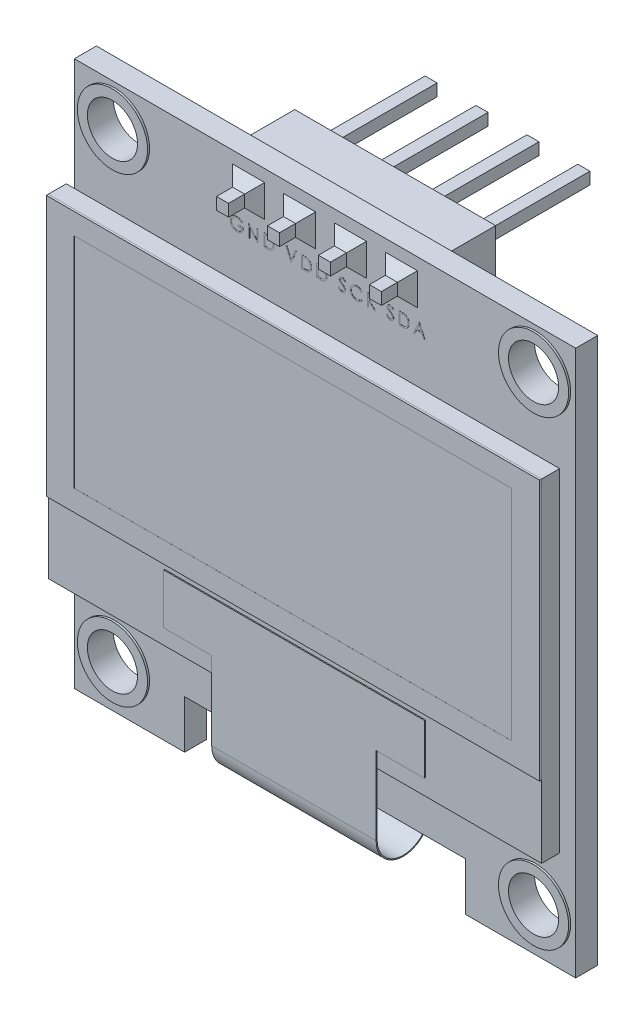
SolidWorks part; units mm, degrees
ref_plane "Front" through (0, 0, 0) normal (0, 0, 1) x (1, 0, 0)
ref_plane "Top" through (0, 0, 0) normal (0, 1, 0) x (1, 0, 0)
ref_plane "Right" through (0, 0, 0) normal (1, 0, 0) x (0, 0, -1)
sketch "Sketch1" plane through (0, 0, 0) normal (0, 0, 1) x (1, 0, 0)
  line L0 (7, -27.2) -> (12.5, -27.2)
  line L1 (-12.5, 0) -> (12.5, 0)
  line L2 (-12.5, 0) -> (-12.5, -27.2)
  line L3 (-12.5, -27.2) -> (-7, -27.2)
  line L4 (12.5, 0) -> (12.5, -27.2)
  line L5 (0, 0) -> (0, -2) construction
  line L6 (-7, -27.2) -> (-7, -24.8)
  line L7 (-7, -24.8) -> (7, -24.8)
  line L8 (7, -27.2) -> (7, -24.8)
  line L9 (-10.5, -2) -> (10.5, -2) construction
  line L10 (-10.5, -2) -> (-10.5, -25) construction
  line L11 (-10.5, -25) -> (10.5, -25) construction
  line L12 (10.5, -2) -> (10.5, -25) construction
  circle A0 centre (-10.5, -2) radius 1.25
  circle A1 centre (10.5, -2) radius 1.25
  circle A2 centre (10.5, -25) radius 1.25
  circle A3 centre (-10.5, -25) radius 1.25
  dimension "D5" = 2.5
  dimension "D1" = 25
  dimension "D2" = 27.2
  dimension "D3" = 5.5
  dimension "D4" = 2.4
  dimension "D6" = 2
  dimension "D7" = 21
  dimension "D8" = 23
extrude "Boss-Extrude1" add sketch "Sketch1" along normal blind 1.1
sketch "Sketch2" plane through (0, 0, 1.1) normal (0, 0, 1) x (1, 0, 0)
  line L0 (-1.57, -1.1) -> (-0.97, -1.1)
  line L1 (-4.11, -1.1) -> (-3.51, -1.1)
  line L2 (-4.11, -1.1) -> (-4.11, -1.7)
  line L3 (-4.11, -1.7) -> (-3.51, -1.7)
  line L4 (-3.51, -1.1) -> (-3.51, -1.7)
  line L5 (-1.57, -1.1) -> (-1.57, -1.7)
  line L6 (-1.57, -1.7) -> (-0.97, -1.7)
  line L7 (-0.97, -1.1) -> (-0.97, -1.7)
  line L8 (0.97, -1.1) -> (1.57, -1.1)
  line L9 (0.97, -1.1) -> (0.97, -1.7)
  line L10 (0.97, -1.7) -> (1.57, -1.7)
  line L11 (1.57, -1.1) -> (1.57, -1.7)
  line L12 (3.51, -1.1) -> (4.11, -1.1)
  line L13 (3.51, -1.1) -> (3.51, -1.7)
  line L14 (3.51, -1.7) -> (4.11, -1.7)
  line L15 (4.11, -1.1) -> (4.11, -1.7)
  line L16 (-0.97, -1.4) -> (0.97, -1.4) construction
  line L17 (0, 0) -> (0, -1.4) construction
  dimension "D2" = 0.6
  dimension "D3" = 2.54
  dimension "D4" = 1.4
  dimension "D1" = 4
extrude "Boss-Extrude2" add sketch "Sketch2" against normal offset from surface 8 and the other way blind 1.3 up to face at (11.75, -25, 0) offset beyond the face yes
chamfer "Chamfer1" distance 0.5 angle 45 16 edges at (-3.81, -1.7, 1.1) (-4.11, -1.4, 1.1) (-3.51, -1.4, 1.1) (-3.81, -1.1, 1.1) (-1.27, -1.7, 1.1) (-1.57, -1.4, 1.1) (-0.97, -1.4, 1.1) (-1.27, -1.1, 1.1) (3.81, -1.7, 1.1) (3.51, -1.4, 1.1) (4.11, -1.4, 1.1) (3.81, -1.1, 1.1) (1.57, -1.4, 1.1) (1.27, -1.7, 1.1) (0.97, -1.4, 1.1) (1.27, -1.1, 1.1)
sketch "Sketch3" plane through (0, 0, 0) normal (0, 0, -1) x (-1, 0, 0)
  line L0 (-5.01, -1.4) -> (-4.11, -1.4) construction
  line L1 (-5.01, -0.2) -> (5.01, -0.2)
  line L2 (-5.01, -0.2) -> (-5.01, -2.6)
  line L3 (-5.01, -2.6) -> (5.01, -2.6)
  line L4 (5.01, -0.2) -> (5.01, -2.6)
  line L5 (-4.11, -1.1) -> (-4.11, -1.7) construction
  line L6 (4.11, -1.4) -> (5.01, -1.4) construction
  line L7 (4.11, -1.7) -> (4.11, -1.1) construction
  line L8 (-3.51, -1.1) -> (-4.11, -1.1) construction
  point P12 (-3.81, -1.1)
  dimension "D1" = 2.4
  dimension "D2" = 1.2
extrude "Boss-Extrude3" add sketch "Sketch3" along normal blind 2.4 separate body
sketch "Sketch4" plane through (0, 0, 1.1) normal (0, 0, 1) x (1, 0, 0)
  line L0 (12.5, 0) -> (-12.5, 0) construction
  line L1 (-12.3, -5) -> (12.3, -5)
  line L2 (-12.3, -5) -> (-12.3, -21.6)
  line L3 (-12.3, -21.6) -> (12.3, -21.6)
  line L4 (12.3, -5) -> (12.3, -21.6)
  point P4 (0, -5)
  dimension "D1" = 24.6
  dimension "D2" = 16.6
  dimension "D3" = 5
extrude "Boss-Extrude4" add sketch "Sketch4" along normal blind 0.9 from offset 0.6
sketch "Sketch5" plane through (0, 0, 2.6) normal (0, 0, 1) x (1, 0, 0)
  line L0 (12.3, -21.6) -> (12.3, -5) construction
  line L1 (-12.3, -5) -> (12.3, -5)
  line L2 (-12.3, -5) -> (-12.3, -18)
  line L3 (-12.3, -18) -> (12.3, -18)
  line L4 (12.3, -5) -> (12.3, -18)
  dimension "D1" = 13
extrude "Boss-Extrude5" add sketch "Sketch5" along normal blind 0.1
sketch "Sketch6" plane through (0, 0, 1.7) normal (0, 0, -1) x (-1, 0, 0)
  line L8 (11.3, -20.6) -> (11.3, -6)
  line L9 (11.3, -6) -> (-11.3, -6)
  line L10 (-11.3, -6) -> (-11.3, -20.6)
  line L11 (-11.3, -20.6) -> (11.3, -20.6)
  line L12 (11.3, -20.6) -> (11.3, -6)
  line L13 (11.3, -6) -> (-11.3, -6)
  line L14 (-11.3, -6) -> (-11.3, -20.6)
  line L15 (-11.3, -20.6) -> (11.3, -20.6)
  dimension "D1" = 1
extrude "Boss-Extrude6" add sketch "Sketch6" along normal up to surface (0.6 mm away) separate body up to face at (-3.81, -1.4, 1.1)
sketch "Sketch7" plane through (0, 0, 0) normal (1, 0, 0) x (0, 0, -1)
  line L0 (-2.6, -18.3) -> (-2.6, -21.6)
  line L1 (-2.6, -21.6) -> (-2.6, -5) construction
  line L3 (-2.6, -21.6) -> (-2.6, -24.7)
  line L4 (0, -19.2) -> (0, -24.7)
  line L5 (0, -27.2) -> (0, 0) construction
  line L6 (-1.3, -26) -> (-1.3, -27.2) construction
  line L7 (-1.3, -27.2) -> (-1.1, -27.2) construction
  line L8 (-1.1, -27.2) -> (0, -27.2) construction
  arc A0 (-2.6, -24.7) -> (0, -24.7) centre (-1.3, -24.7) ccw
  dimension "D1" = 1.2
  dimension "D2" = 0.3
  dimension "D3" = 8
extrude "Extrude-Thin1" add sketch "Sketch7" along normal mid plane 21 separate body thin
ref_plane "Plane1" through (0, 0, 1.3) normal (0, 0, 1) x (1, 0, 0)
sketch "Sketch9" plane through (0, 0, 1.3) normal (0, 0, 1) x (1, 0, 0)
  line L0 (-6.5, -18.3) -> (-6.5, -20.8)
  line L1 (10.5, -18.3) -> (-10.5, -18.3) construction
  line L2 (-6.5, -20.8) -> (-4.1, -20.8)
  line L3 (-4.1, -20.8) -> (-4.1, -26.05)
  line L4 (-10.5, -26.05) -> (10.5, -26.05) construction
  line L5 (-4.1, -26.05) -> (4.1, -26.05)
  line L6 (4.1, -26.05) -> (4.1, -20.8)
  line L7 (4.1, -20.8) -> (6.5, -20.8)
  line L8 (6.5, -20.8) -> (6.5, -18.3)
  line L9 (6.5, -18.3) -> (-6.5, -18.3)
  point P4 (0, -18.3)
  dimension "D1" = 13
  dimension "D2" = 2.5
  dimension "D3" = 8.2
extrude "Cut-Extrude1" cut sketch "Sketch9" along normal blind 21 flip side to cut
sketch "Sketch10" plane through (0, 0, 1.3) normal (0, 0, 1) x (1, 0, 0)
  line L1 (4.1, -26.05) -> (4.1, -25.55)
  line L2 (4.1, -25.55) -> (10.5, -22.2)
  line L3 (10.5, -19.2) -> (10.5, -24.7) construction
  line L4 (10.5, -22.2) -> (10.5, -19.2)
  line L5 (10.5, -19.2) -> (-10.5, -19.2)
  line L6 (-10.5, -19.2) -> (-10.5, -24.7) construction
  line L7 (-10.5, -19.2) -> (-10.5, -22.2)
  line L8 (-10.5, -22.2) -> (-4.1, -25.55)
  line L9 (-4.1, -25.55) -> (-4.1, -26.05)
  line L10 (-4.1, -26.05) -> (4.1, -26.05)
  line L12 (10.5, -19.2) -> (-10.5, -19.2) construction
  dimension "D1" = 3
  dimension "D2" = 0.5
extrude "Cut-Extrude2" cut sketch "Sketch10" against normal blind 21 flip side to cut
sketch "Sketch11" plane through (0, 0, 2.7) normal (0, 0, 1) x (1, 0, 0)
  line L4 (0, -5) -> (0, -6.0476) construction
  line L5 (12.3, -5) -> (-12.3, -5) construction
  line L6 (0, -16.9524) -> (0, -18) construction
  line L7 (-12.3, -18) -> (12.3, -18) construction
  line L8 (0, -6.0476) -> (-10.9049, -6.0476) construction
  line L12 (-10.9049, -6.0476) -> (-10.9049, -16.9524)
  line L13 (-10.9049, -16.9524) -> (10.9049, -16.9524)
  line L14 (10.9049, -16.9524) -> (10.9049, -6.0476)
  line L15 (10.9049, -6.0476) -> (-10.9049, -6.0476)
  dimension "D1" = 24.384
extrude "Cut-Extrude3" cut sketch "Sketch11" against normal blind 0.001
sketch "Sketch12" plane through (0, 0, 1.1) normal (0, 0, 1) x (1, 0, 0)
  text T0 "GND VDD SCK SDA" font "Century Gothic" height 0.62
extrude "Boss-Extrude7" add sketch "Sketch12" along normal blind 0.005 separate body
sketch "Sketch13" plane through (0, 0, 0) normal (0, 0, -1) x (-1, 0, 0)
  line L1 (-9.3258, -6.7901) -> (-7.836, -6.7901)
  line L2 (-9.3258, -6.7901) -> (-9.3258, -7.7287)
  line L3 (-9.3258, -7.7287) -> (-7.836, -7.7287)
  line L4 (-7.836, -6.7901) -> (-7.836, -7.7287)
  line L5 (-9.3258, -9.2334) -> (-7.836, -9.2334)
  line L6 (-9.3258, -9.2334) -> (-9.3258, -10.1571)
  line L7 (-9.3258, -10.1571) -> (-7.836, -10.1571)
  line L8 (-7.836, -9.2334) -> (-7.836, -10.1571)
  line L9 (-0.2827, -4.5107) -> (1.2816, -4.5107)
  line L10 (-0.2827, -4.5107) -> (-0.2827, -5.4344)
  line L11 (-0.2827, -5.4344) -> (1.2816, -5.4344)
  line L12 (1.2816, -4.5107) -> (1.2816, -5.4344)
  line L13 (1.6392, -6.6411) -> (2.9651, -6.6411)
  line L14 (1.6392, -6.6411) -> (1.6392, -7.7287)
  line L15 (1.6392, -7.7287) -> (2.9651, -7.7287)
  line L16 (2.9651, -6.6411) -> (2.9651, -7.7287)
  line L17 (0.4995, -8.3544) -> (1.952, -8.3544)
  line L18 (0.4995, -8.3544) -> (0.4995, -11.4085)
  line L19 (0.4995, -11.4085) -> (1.952, -11.4085)
  line L20 (1.952, -8.3544) -> (1.952, -11.4085)
  line L21 (8.5504, -8.149) -> (9.9556, -8.149)
  line L22 (8.5504, -8.149) -> (8.5504, -9.2334)
  line L23 (8.5504, -9.2334) -> (9.9556, -9.2334)
  line L24 (9.9556, -8.149) -> (9.9556, -9.2334)
  line L25 (8.5504, -10.3363) -> (9.9556, -10.3363)
  line L26 (8.5504, -10.3363) -> (8.5504, -11.4085)
  line L27 (8.5504, -11.4085) -> (9.9556, -11.4085)
  line L28 (9.9556, -10.3363) -> (9.9556, -11.4085)
  line L29 (-11.6812, -12.9613) -> (-10.7369, -12.9613)
  line L30 (-11.6812, -12.9613) -> (-11.6812, -14.6446)
  line L31 (-11.6812, -14.6446) -> (-10.7369, -14.6446)
  line L32 (-10.7369, -12.9613) -> (-10.7369, -14.6446)
  line L33 (-9.7105, -12.9613) -> (-8.7457, -12.9613)
  line L34 (-9.7105, -12.9613) -> (-9.7105, -14.6446)
  line L35 (-9.7105, -14.6446) -> (-8.7457, -14.6446)
  line L36 (-8.7457, -12.9613) -> (-8.7457, -14.6446)
  line L37 (-7.1651, -12.9613) -> (-6.2413, -12.9613)
  line L38 (-7.1651, -12.9613) -> (-7.1651, -14.6446)
  line L39 (-7.1651, -14.6446) -> (-6.2413, -14.6446)
  line L40 (-6.2413, -12.9613) -> (-6.2413, -14.6446)
  line L41 (-4.0859, -12.9613) -> (-3.2032, -12.9613)
  line L42 (-4.0859, -12.9613) -> (-4.0859, -14.6446)
  line L43 (-4.0859, -14.6446) -> (-3.2032, -14.6446)
  line L44 (-3.2032, -12.9613) -> (-3.2032, -14.6446)
  line L45 (-1.6636, -12.9613) -> (-0.8014, -12.9613)
  line L46 (-1.6636, -12.9613) -> (-1.6636, -14.6446)
  line L47 (-1.6636, -14.6446) -> (-0.8014, -14.6446)
  line L48 (-0.8014, -12.9613) -> (-0.8014, -14.6446)
  line L49 (0.4995, -12.9613) -> (1.4361, -12.9613)
  line L50 (0.4995, -12.9613) -> (0.4995, -14.6446)
  line L51 (0.4995, -14.6446) -> (1.4361, -14.6446)
  line L52 (1.4361, -12.9613) -> (1.4361, -14.6446)
  line L53 (2.7704, -12.9613) -> (3.6121, -12.9613)
  line L54 (2.7704, -12.9613) -> (2.7704, -14.6446)
  line L55 (2.7704, -14.6446) -> (3.6121, -14.6446)
  line L56 (3.6121, -12.9613) -> (3.6121, -14.6446)
  line L57 (5.1311, -12.9613) -> (5.9933, -12.9613)
  line L58 (5.1311, -12.9613) -> (5.1311, -14.6446)
  line L59 (5.1311, -14.6446) -> (5.9933, -14.6446)
  line L60 (5.9933, -12.9613) -> (5.9933, -14.6446)
  line L61 (7.7587, -12.9613) -> (8.5504, -12.9613)
  line L62 (7.7587, -12.9613) -> (7.7587, -14.6446)
  line L63 (7.7587, -14.6446) -> (8.5504, -14.6446)
  line L64 (8.5504, -12.9613) -> (8.5504, -14.6446)
  line L65 (9.9556, -12.9613) -> (11.0432, -12.9613)
  line L66 (9.9556, -12.9613) -> (9.9556, -14.6446)
  line L67 (9.9556, -14.6446) -> (11.0432, -14.6446)
  line L68 (11.0432, -12.9613) -> (11.0432, -14.6446)
extrude "Boss-Extrude8" add sketch "Sketch13" along normal blind 0.6
sketch "Sketch14" plane through (0, 0, 0) normal (0, 0, -1) x (-1, 0, 0)
  line L0 (-10.5, -19.2) -> (10.5, -19.2) construction
  line L1 (-10.5, -17.5) -> (-10.23, -17.5)
  line L2 (-10.5, -17.5) -> (-10.5, -19.2)
  line L3 (-10.5, -19.2) -> (-10.23, -19.2)
  line L4 (-10.23, -17.5) -> (-10.23, -19.2)
  line L5 (-9.9685, -17.5) -> (-9.9685, -19.2)
  line L6 (-9.9685, -17.5) -> (-9.6985, -17.5)
  line L7 (-9.6985, -17.5) -> (-9.6985, -19.2)
  line L8 (-9.9685, -19.2) -> (-9.6985, -19.2)
  line L9 (-9.4369, -17.5) -> (-9.4369, -19.2)
  line L10 (-9.4369, -17.5) -> (-9.1669, -17.5)
  line L11 (-9.1669, -17.5) -> (-9.1669, -19.2)
  line L12 (-9.4369, -19.2) -> (-9.1669, -19.2)
  line L13 (-8.9054, -17.5) -> (-8.9054, -19.2)
  line L14 (-8.9054, -17.5) -> (-8.6354, -17.5)
  line L15 (-8.6354, -17.5) -> (-8.6354, -19.2)
  line L16 (-8.9054, -19.2) -> (-8.6354, -19.2)
  line L17 (-8.3738, -17.5) -> (-8.3738, -19.2)
  line L18 (-8.3738, -17.5) -> (-8.1038, -17.5)
  line L19 (-8.1038, -17.5) -> (-8.1038, -19.2)
  line L20 (-8.3738, -19.2) -> (-8.1038, -19.2)
  line L21 (-7.8423, -17.5) -> (-7.8423, -19.2)
  line L22 (-7.8423, -17.5) -> (-7.5723, -17.5)
  line L23 (-7.5723, -17.5) -> (-7.5723, -19.2)
  line L24 (-7.8423, -19.2) -> (-7.5723, -19.2)
  line L25 (-7.3108, -17.5) -> (-7.3108, -19.2)
  line L26 (-7.3108, -17.5) -> (-7.0408, -17.5)
  line L27 (-7.0408, -17.5) -> (-7.0408, -19.2)
  line L28 (-7.3108, -19.2) -> (-7.0408, -19.2)
  line L29 (-6.7792, -17.5) -> (-6.7792, -19.2)
  line L30 (-6.7792, -17.5) -> (-6.5092, -17.5)
  line L31 (-6.5092, -17.5) -> (-6.5092, -19.2)
  line L32 (-6.7792, -19.2) -> (-6.5092, -19.2)
  line L33 (-6.2477, -17.5) -> (-6.2477, -19.2)
  line L34 (-6.2477, -17.5) -> (-5.9777, -17.5)
  line L35 (-5.9777, -17.5) -> (-5.9777, -19.2)
  line L36 (-6.2477, -19.2) -> (-5.9777, -19.2)
  line L37 (-5.7162, -17.5) -> (-5.7162, -19.2)
  line L38 (-5.7162, -17.5) -> (-5.4462, -17.5)
  line L39 (-5.4462, -17.5) -> (-5.4462, -19.2)
  line L40 (-5.7162, -19.2) -> (-5.4462, -19.2)
  line L41 (-5.1846, -17.5) -> (-5.1846, -19.2)
  line L42 (-5.1846, -17.5) -> (-4.9146, -17.5)
  line L43 (-4.9146, -17.5) -> (-4.9146, -19.2)
  line L44 (-5.1846, -19.2) -> (-4.9146, -19.2)
  line L45 (-4.6531, -17.5) -> (-4.6531, -19.2)
  line L46 (-4.6531, -17.5) -> (-4.3831, -17.5)
  line L47 (-4.3831, -17.5) -> (-4.3831, -19.2)
  line L48 (-4.6531, -19.2) -> (-4.3831, -19.2)
  line L49 (-4.1215, -17.5) -> (-4.1215, -19.2)
  line L50 (-4.1215, -17.5) -> (-3.8515, -17.5)
  line L51 (-3.8515, -17.5) -> (-3.8515, -19.2)
  line L52 (-4.1215, -19.2) -> (-3.8515, -19.2)
  line L53 (-3.59, -17.5) -> (-3.59, -19.2)
  line L54 (-3.59, -17.5) -> (-3.32, -17.5)
  line L55 (-3.32, -17.5) -> (-3.32, -19.2)
  line L56 (-3.59, -19.2) -> (-3.32, -19.2)
  line L57 (-3.0585, -17.5) -> (-3.0585, -19.2)
  line L58 (-3.0585, -17.5) -> (-2.7885, -17.5)
  line L59 (-2.7885, -17.5) -> (-2.7885, -19.2)
  line L60 (-3.0585, -19.2) -> (-2.7885, -19.2)
  line L61 (-2.5269, -17.5) -> (-2.5269, -19.2)
  line L62 (-2.5269, -17.5) -> (-2.2569, -17.5)
  line L63 (-2.2569, -17.5) -> (-2.2569, -19.2)
  line L64 (-2.5269, -19.2) -> (-2.2569, -19.2)
  line L65 (-1.9954, -17.5) -> (-1.9954, -19.2)
  line L66 (-1.9954, -17.5) -> (-1.7254, -17.5)
  line L67 (-1.7254, -17.5) -> (-1.7254, -19.2)
  line L68 (-1.9954, -19.2) -> (-1.7254, -19.2)
  line L69 (-1.4638, -17.5) -> (-1.4638, -19.2)
  line L70 (-1.4638, -17.5) -> (-1.1938, -17.5)
  line L71 (-1.1938, -17.5) -> (-1.1938, -19.2)
  line L72 (-1.4638, -19.2) -> (-1.1938, -19.2)
  line L73 (-0.9323, -17.5) -> (-0.9323, -19.2)
  line L74 (-0.9323, -17.5) -> (-0.6623, -17.5)
  line L75 (-0.6623, -17.5) -> (-0.6623, -19.2)
  line L76 (-0.9323, -19.2) -> (-0.6623, -19.2)
  line L77 (-0.4008, -17.5) -> (-0.4008, -19.2)
  line L78 (-0.4008, -17.5) -> (-0.1308, -17.5)
  line L79 (-0.1308, -17.5) -> (-0.1308, -19.2)
  line L80 (-0.4008, -19.2) -> (-0.1308, -19.2)
  line L81 (0.1308, -17.5) -> (0.1308, -19.2)
  line L82 (0.1308, -17.5) -> (0.4008, -17.5)
  line L83 (0.4008, -17.5) -> (0.4008, -19.2)
  line L84 (0.1308, -19.2) -> (0.4008, -19.2)
  line L85 (0.6623, -17.5) -> (0.6623, -19.2)
  line L86 (0.6623, -17.5) -> (0.9323, -17.5)
  line L87 (0.9323, -17.5) -> (0.9323, -19.2)
  line L88 (0.6623, -19.2) -> (0.9323, -19.2)
  line L89 (1.1938, -17.5) -> (1.1938, -19.2)
  line L90 (1.1938, -17.5) -> (1.4638, -17.5)
  line L91 (1.4638, -17.5) -> (1.4638, -19.2)
  line L92 (1.1938, -19.2) -> (1.4638, -19.2)
  line L93 (1.7254, -17.5) -> (1.7254, -19.2)
  line L94 (1.7254, -17.5) -> (1.9954, -17.5)
  line L95 (1.9954, -17.5) -> (1.9954, -19.2)
  line L96 (1.7254, -19.2) -> (1.9954, -19.2)
  line L97 (2.2569, -17.5) -> (2.2569, -19.2)
  line L98 (2.2569, -17.5) -> (2.5269, -17.5)
  line L99 (2.5269, -17.5) -> (2.5269, -19.2)
  line L100 (2.2569, -19.2) -> (2.5269, -19.2)
  line L101 (2.7885, -17.5) -> (2.7885, -19.2)
  line L102 (2.7885, -17.5) -> (3.0585, -17.5)
  line L103 (3.0585, -17.5) -> (3.0585, -19.2)
  line L104 (2.7885, -19.2) -> (3.0585, -19.2)
  line L105 (3.32, -17.5) -> (3.32, -19.2)
  line L106 (3.32, -17.5) -> (3.59, -17.5)
  line L107 (3.59, -17.5) -> (3.59, -19.2)
  line L108 (3.32, -19.2) -> (3.59, -19.2)
  line L109 (3.8515, -17.5) -> (3.8515, -19.2)
  line L110 (3.8515, -17.5) -> (4.1215, -17.5)
  line L111 (4.1215, -17.5) -> (4.1215, -19.2)
  line L112 (3.8515, -19.2) -> (4.1215, -19.2)
  line L113 (4.3831, -17.5) -> (4.3831, -19.2)
  line L114 (4.3831, -17.5) -> (4.6531, -17.5)
  line L115 (4.6531, -17.5) -> (4.6531, -19.2)
  line L116 (4.3831, -19.2) -> (4.6531, -19.2)
  line L117 (4.9146, -17.5) -> (4.9146, -19.2)
  line L118 (4.9146, -17.5) -> (5.1846, -17.5)
  line L119 (5.1846, -17.5) -> (5.1846, -19.2)
  line L120 (4.9146, -19.2) -> (5.1846, -19.2)
  line L121 (5.4462, -17.5) -> (5.4462, -19.2)
  line L122 (5.4462, -17.5) -> (5.7162, -17.5)
  line L123 (5.7162, -17.5) -> (5.7162, -19.2)
  line L124 (5.4462, -19.2) -> (5.7162, -19.2)
  line L125 (5.9777, -17.5) -> (5.9777, -19.2)
  line L126 (5.9777, -17.5) -> (6.2477, -17.5)
  line L127 (6.2477, -17.5) -> (6.2477, -19.2)
  line L128 (5.9777, -19.2) -> (6.2477, -19.2)
  line L129 (6.5092, -17.5) -> (6.5092, -19.2)
  line L130 (6.5092, -17.5) -> (6.7792, -17.5)
  line L131 (6.7792, -17.5) -> (6.7792, -19.2)
  line L132 (6.5092, -19.2) -> (6.7792, -19.2)
  line L133 (7.0408, -17.5) -> (7.0408, -19.2)
  line L134 (7.0408, -17.5) -> (7.3108, -17.5)
  line L135 (7.3108, -17.5) -> (7.3108, -19.2)
  line L136 (7.0408, -19.2) -> (7.3108, -19.2)
  line L137 (7.5723, -17.5) -> (7.5723, -19.2)
  line L138 (7.5723, -17.5) -> (7.8423, -17.5)
  line L139 (7.8423, -17.5) -> (7.8423, -19.2)
  line L140 (7.5723, -19.2) -> (7.8423, -19.2)
  line L141 (8.1038, -17.5) -> (8.1038, -19.2)
  line L142 (8.1038, -17.5) -> (8.3738, -17.5)
  line L143 (8.3738, -17.5) -> (8.3738, -19.2)
  line L144 (8.1038, -19.2) -> (8.3738, -19.2)
  line L145 (8.6354, -17.5) -> (8.6354, -19.2)
  line L146 (8.6354, -17.5) -> (8.9054, -17.5)
  line L147 (8.9054, -17.5) -> (8.9054, -19.2)
  line L148 (8.6354, -19.2) -> (8.9054, -19.2)
  line L149 (9.1669, -17.5) -> (9.1669, -19.2)
  line L150 (9.1669, -17.5) -> (9.4369, -17.5)
  line L151 (9.4369, -17.5) -> (9.4369, -19.2)
  line L152 (9.1669, -19.2) -> (9.4369, -19.2)
  line L153 (9.6985, -17.5) -> (9.6985, -19.2)
  line L154 (9.6985, -17.5) -> (9.9685, -17.5)
  line L155 (9.9685, -17.5) -> (9.9685, -19.2)
  line L156 (9.6985, -19.2) -> (9.9685, -19.2)
  line L157 (10.23, -17.5) -> (10.23, -19.2)
  line L158 (10.23, -17.5) -> (10.5, -17.5)
  line L159 (10.5, -17.5) -> (10.5, -19.2)
  line L160 (10.23, -19.2) -> (10.5, -19.2)
  line L161 (-10.5, -19.2) -> (-10.5, -22.2) construction
  dimension "D2" = 1.7
  dimension "D3" = 0.27
  dimension "D1" = 40
extrude "Boss-Extrude9" add sketch "Sketch14" along normal up to vertex (0.05 mm away) separate body
sketch "Sketch15" plane through (0, 0, 1.1) normal (0, 0, 1) x (1, 0, 0)
  circle A1 centre (10.5, -2) radius 1.25 construction
  circle A2 centre (10.5, -25) radius 1.25 construction
  circle A3 centre (-10.5, -25) radius 1.25 construction
  circle A4 centre (-10.5, -2) radius 1.25 construction
  circle A9 centre (-10.5, -2) radius 1.25
  circle A10 centre (-10.5, -25) radius 1.25
  circle A11 centre (10.5, -25) radius 1.25
  circle A12 centre (10.5, -2) radius 1.25
  circle A13 centre (-10.5, -2) radius 1.75
  circle A14 centre (-10.5, -25) radius 1.75
  circle A15 centre (10.5, -25) radius 1.75
  circle A16 centre (10.5, -2) radius 1.75
  dimension "D1" = 0.5
extrude "Boss-Extrude10" add sketch "Sketch15" along normal blind 0.1
sketch "Sketch16" plane through (0, 0, 0) normal (0, 0, -1) x (-1, 0, 0)
  circle A1 centre (10.5, -25) radius 1.75
  circle A2 centre (10.5, -25) radius 1.75
  circle A3 centre (10.5, -2) radius 1.75
  circle A4 centre (10.5, -2) radius 1.75
  circle A5 centre (-10.5, -2) radius 1.25
  circle A6 centre (-10.5, -2) radius 1.25
  circle A7 centre (-10.5, -25) radius 1.25
  circle A8 centre (-10.5, -25) radius 1.25
  circle A9 centre (10.5, -25) radius 1.25
  circle A10 centre (10.5, -25) radius 1.25
  circle A11 centre (10.5, -2) radius 1.25
  circle A12 centre (10.5, -2) radius 1.25
  circle A13 centre (-10.5, -2) radius 1.75
  circle A14 centre (-10.5, -2) radius 1.75
  circle A15 centre (-10.5, -25) radius 1.75
  circle A16 centre (-10.5, -25) radius 1.75
  dimension "D1" = 0
  dimension "D2" = 0
  dimension "D3" = 0
  dimension "D4" = 0
  dimension "D5" = 0
  dimension "D6" = 0
  dimension "D7" = 0
  dimension "D8" = 0
extrude "Boss-Extrude11" add sketch "Sketch16" along normal blind 0.1
